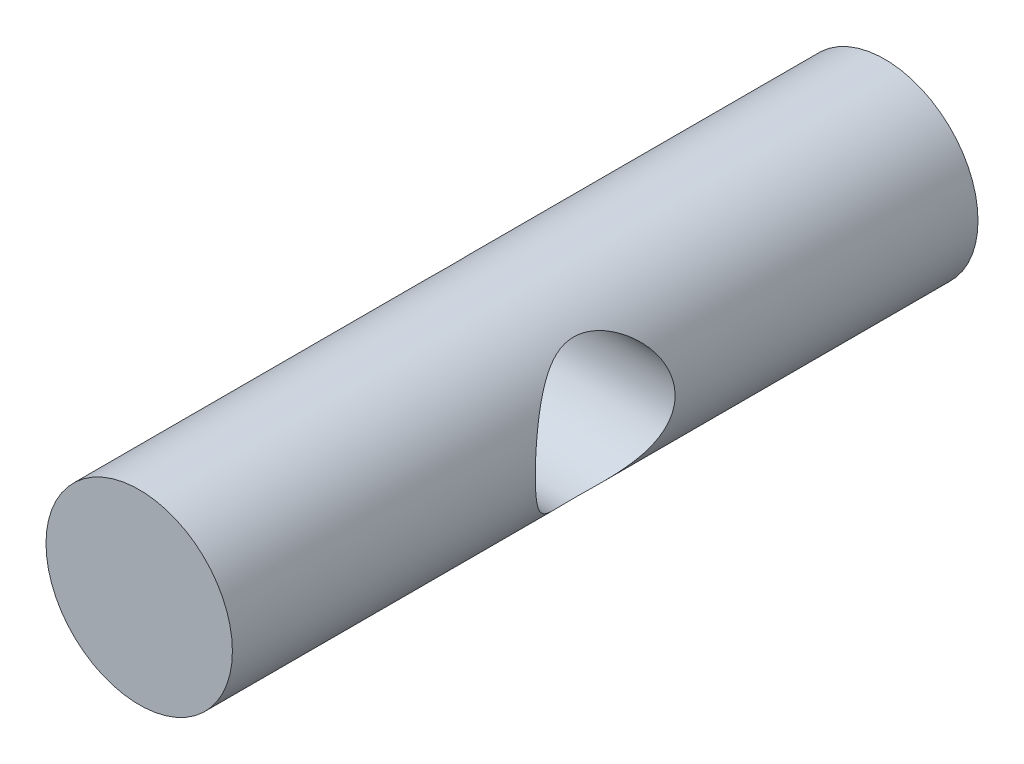
SolidWorks part; units mm, degrees
ref_plane "Front Plane" through (0, 0, 0) normal (0, 0, 1) x (1, 0, 0)
ref_plane "Top Plane" through (0, 0, 0) normal (0, 1, 0) x (1, 0, 0)
ref_plane "Right Plane" through (0, 0, 0) normal (1, 0, 0) x (0, 0, -1)
sketch "Sketch1" plane through (0, 0, 0) normal (0, 0, 1) x (1, 0, 0)
  circle A0 centre (0, 0) radius 10
  dimension "D1" = 20
extrude "Boss-Extrude1" add sketch "Sketch1" along normal blind 80
sketch "Sketch2" plane through (0, 0, 0) normal (1, 0, 0) x (0, 0, -1)
  line L0 (-80, 10) -> (-80, -10) construction
  circle A0 centre (-40, 0) radius 7.5
  dimension "D1" = 40
  dimension "D2" = 15
extrude "Cut-Extrude1" cut sketch "Sketch2" against normal blind 14 and the other way blind 13
